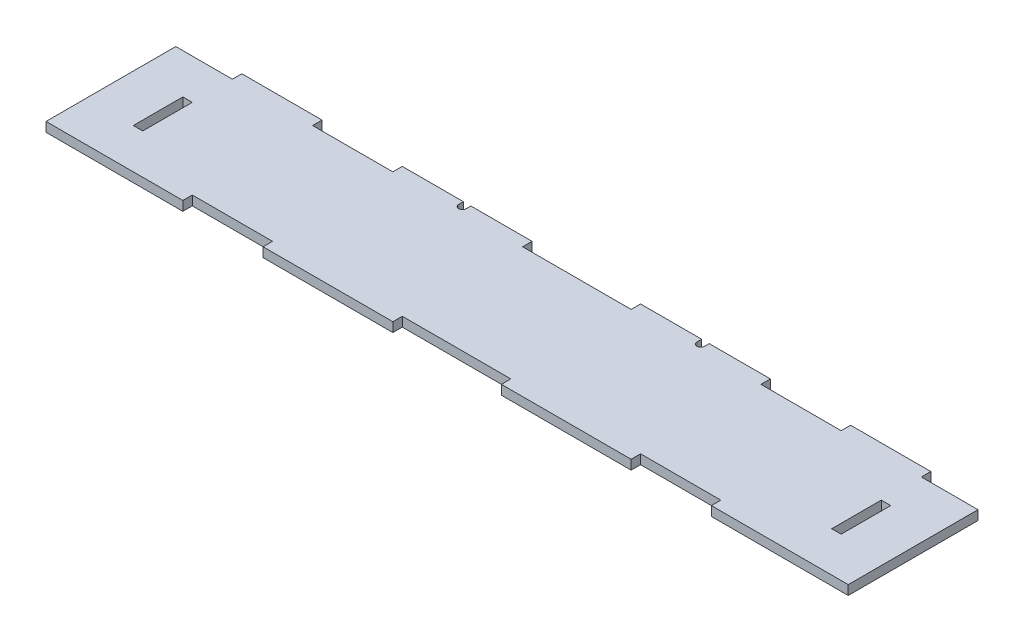
SolidWorks part; units mm, degrees
ref_plane "Front" through (0, 0, 0) normal (0, 0, 1) x (1, 0, 0)
ref_plane "Top" through (0, 0, 0) normal (0, 1, 0) x (1, 0, 0)
ref_plane "Right" through (0, 0, 0) normal (1, 0, 0) x (0, 0, -1)
sketch "Sketch1" plane through (0, 0, 0) normal (0, 1, 0) x (1, 0, 0)
  line L0 (170, 25.5) -> (-170, 25.5) construction
  line L1 (170, -29.5) -> (-170, -29.5)
  line L2 (170, -29.5) -> (170, 29.5)
  line L3 (170, 29.5) -> (-48.9, 29.5)
  line L4 (-170, -29.5) -> (-170, 29.5)
  line L5 (170, -29.5) -> (-170, 29.5) construction
  line L6 (170, 29.5) -> (-170, -29.5) construction
  line L7 (-146, 29.5) -> (-146, -29.5) construction
  line L9 (150, 29.5) -> (150, -29.5) construction
  line L11 (-150, 29.5) -> (-150, -29.5) construction
  line L12 (150, 29.5) -> (-150, -29.5) construction
  line L13 (150, -29.5) -> (-150, 29.5) construction
  line L14 (146, 29.5) -> (146, -29.5) construction
  line L15 (-150, -12.5) -> (-146, -12.5)
  line L16 (-150, 8.5) -> (-146, 8.5)
  line L17 (-150, 8.5) -> (-150, -12.5)
  line L18 (-146, 8.5) -> (-146, -12.5)
  line L19 (0, -29.5) -> (0, 29.5) construction
  line L20 (146, 8.5) -> (146, -12.5)
  line L21 (150, 8.5) -> (150, -12.5)
  line L22 (150, 8.5) -> (146, 8.5)
  line L23 (150, -12.5) -> (146, -12.5)
  line L24 (-112, 25.5) -> (-112, 29.5)
  line L25 (-78, 29.5) -> (-78, 25.5)
  line L26 (-78, 25.5) -> (-112, 25.5)
  line L27 (-23, 29.5) -> (-23, 25.5)
  line L28 (-23, 25.5) -> (23, 25.5)
  line L29 (-48.9, 29.5) -> (-48.9, 27.5)
  line L30 (-52.1, 29.5) -> (-52.1, 27.5)
  line L31 (-52.1, 29.5) -> (-170, 29.5)
  line L32 (170, 29.5) -> (-170, 29.5) construction
  line L34 (52.1, 29.5) -> (52.1, 27.5)
  line L35 (48.9, 29.5) -> (48.9, 27.5)
  line L36 (23, 29.5) -> (23, 25.5)
  line L37 (78, 25.5) -> (112, 25.5)
  line L38 (78, 29.5) -> (78, 25.5)
  line L39 (112, 25.5) -> (112, 29.5)
  arc A0 (52.1, 27.5) -> (48.9, 27.5) centre (50.5, 27.5) cw
  arc A1 (-52.1, 27.5) -> (-48.9, 27.5) centre (-50.5, 27.5) ccw
  point P0 (0, 0)
  point P8 (0, 0)
  point P35 (-50.5, 29.9024)
  point P46 (0, 25.5)
  point P51 (50.5, 29.9024)
  dimension "D1" = 340
  dimension "D2" = 59
  dimension "D3" = 4
  dimension "D4" = 300
  dimension "D7" = 17
  dimension "D8" = 21
  dimension "D9" = 1.6
  dimension "D10" = 38
  dimension "D11" = 34
  dimension "D12" = 27.5
  dimension "D13" = 55
  dimension "D14" = 3.2
  dimension "D5" = 4
  dimension "D6" = 4
extrude "Boss-Extrude1" add sketch "Sketch1" along normal blind 4 contours A1 L30 L31 L25 L26 L24 L4 L1 L2 L3 L39 L37 L38 L34 A0 L35 L36 L28 L27 L29 L16 L18 L15 L17 L21 L23 L20 L22
sketch "Sketch3" plane through (0, 0, 0) normal (0, -1, 0) x (1, 0, 0)
  line L0 (-112, 29.5) -> (-112, 25.5)
  line L1 (-78, 25.5) -> (-78, 29.5)
  line L2 (-78, 29.5) -> (-112, 29.5)
  line L3 (-23, 25.5) -> (-23, 29.5)
  line L4 (-23, 29.5) -> (23, 29.5)
  line L5 (23, 25.5) -> (23, 29.5)
  line L6 (78, 29.5) -> (112, 29.5)
  line L7 (78, 25.5) -> (78, 29.5)
  line L8 (112, 29.5) -> (112, 25.5)
  line L9 (112, 25.5) -> (-112, 25.5) construction
  line L10 (-146, -8.5) -> (-146, 12.5) construction
  line L11 (170, 29.5) -> (170, -29.5) construction
  line L12 (-112, 25.5) -> (-78, 25.5)
  line L13 (-23, 25.5) -> (23, 25.5)
  line L14 (78, 25.5) -> (112, 25.5)
  line L15 (170, 29.5) -> (-170, 29.5) construction
  line L16 (-170, -29.5) -> (-146, -29.5)
  line L17 (-170, -29.5) -> (-170, -25.5)
  line L18 (-170, -25.5) -> (-146, -25.5)
  line L19 (-146, -29.5) -> (-146, -25.5)
  line L20 (-158, -25.5) -> (-158, -29.5) construction
  line L21 (-170, -27.5) -> (-146, -27.5) construction
  line L22 (170, -29.5) -> (146, -29.5)
  line L23 (170, -29.5) -> (170, -25.5)
  line L24 (170, -25.5) -> (146, -25.5)
  line L25 (146, -29.5) -> (146, -25.5)
  line L26 (158, -25.5) -> (158, -29.5) construction
  line L27 (170, -27.5) -> (146, -27.5) construction
  line L28 (170, -29.5) -> (112, -29.5) construction
  line L29 (-112, -29.5) -> (-170, -29.5) construction
  line L30 (-170, 29.5) -> (-170, -29.5) construction
  point P6 (-52.2527, -14.7367)
  point P9 (0, 29.5)
  point P14 (48.7473, -14.7367)
  point P183 (-158, -27.5)
  point P204 (158, -27.5)
  dimension "D1" = 34
  dimension "D2" = 46
  dimension "D3" = 4
  dimension "D4" = 55
  dimension "D5" = 55
  dimension "D6" = 34
  dimension "D7" = 34
  dimension "D8" = 4
  dimension "D9" = 24
  dimension "D10" = 4
  dimension "D11" = 24
extrude "Cut-Extrude1" cut sketch "Sketch3" against normal up to next
